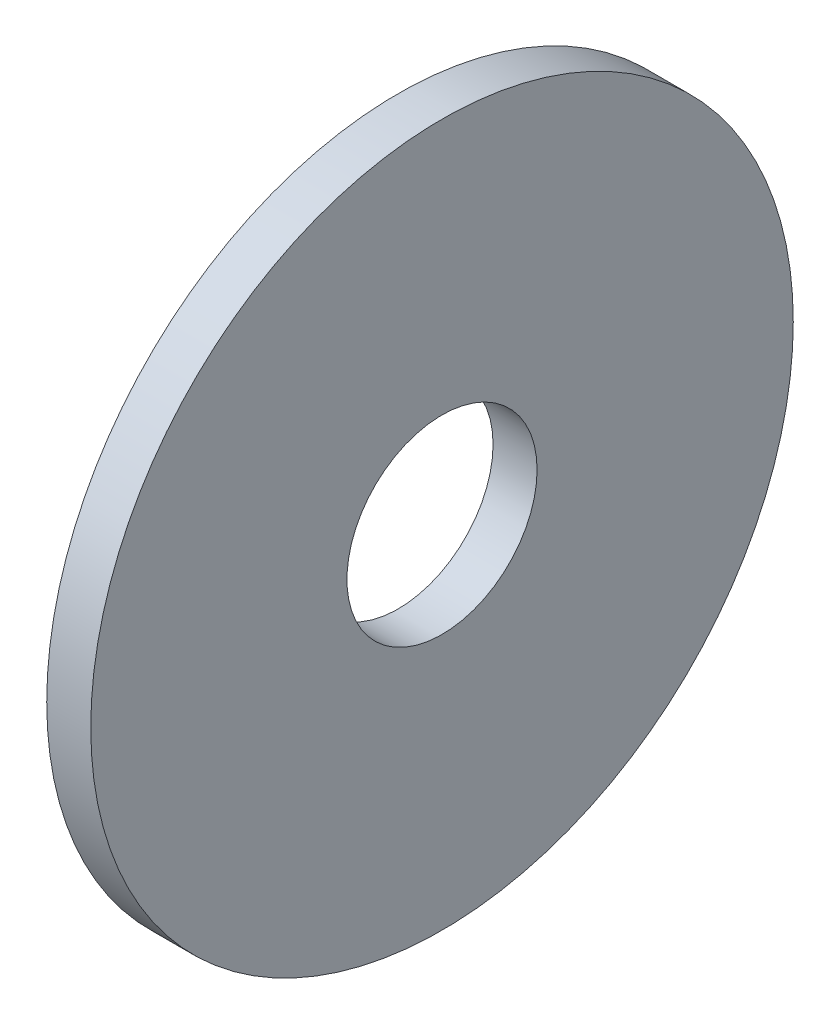
SolidWorks part; units mm, degrees
ref_plane "Front Plane" through (0, 0, 0) normal (0, 0, 1) x (1, 0, 0)
ref_plane "Top Plane" through (0, 0, 0) normal (0, 1, 0) x (1, 0, 0)
ref_plane "Right Plane" through (0, 0, 0) normal (1, 0, 0) x (0, 0, -1)
sketch "Sketch1" plane through (0, 0, 0) normal (1, 0, 0) x (0, 0, -1)
  circle A0 centre (0, 0) radius 9.525
  circle A1 centre (0, 0) radius 2.5781
  dimension "OD" = 19.05
  dimension "ID" = 5.1562
extrude "Boss-Extrude1" add sketch "Sketch1" along normal blind 1.1938
